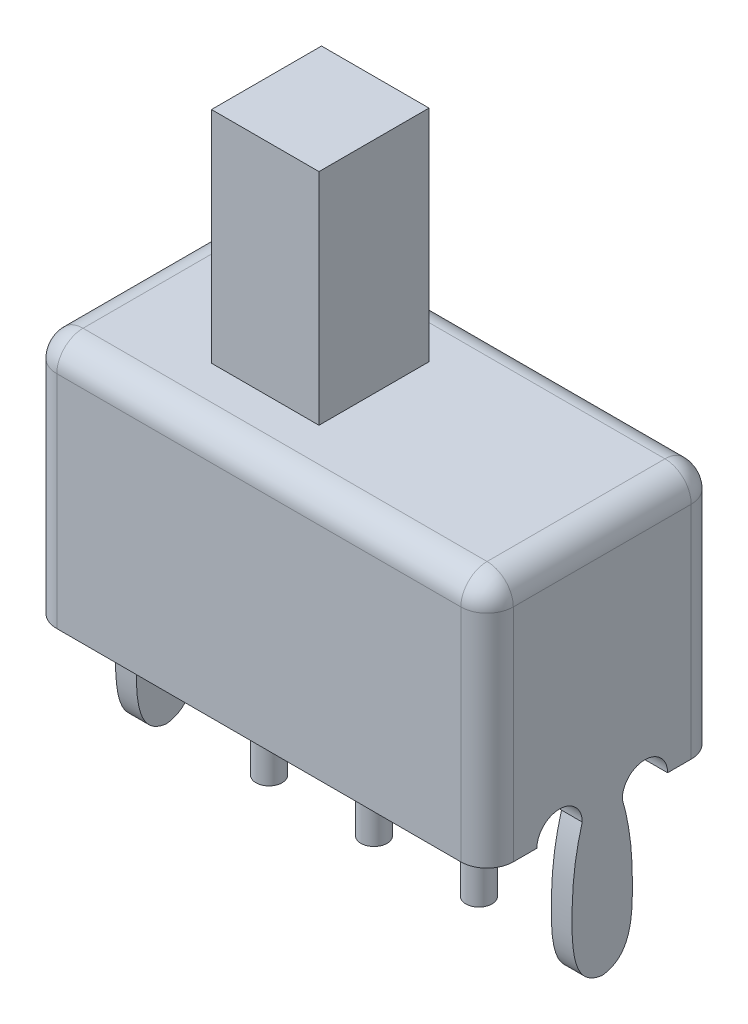
SolidWorks part; units mm, degrees
ref_plane "Front" through (0, 0, 0) normal (0, 0, 1) x (1, 0, 0)
ref_plane "Top" through (0, 0, 0) normal (0, 1, 0) x (1, 0, 0)
ref_plane "Right" through (0, 0, 0) normal (1, 0, 0) x (0, 0, -1)
sketch "Эскиз1" plane through (0, 0, 0) normal (1, 0, 0) x (0, 0, -1)
  line L0 (-1.0075, 7.598) -> (0.9925, 7.598) construction
  line L1 (-2.1951, 0) -> (-2.1951, 4.2075)
  line L2 (-1.6951, 4.7075) -> (-1.0484, 4.7075)
  line L3 (-1.0484, 4.7075) -> (-1.0484, 8.8947)
  line L4 (-1.0484, 8.8947) -> (1.0484, 8.8947)
  line L5 (-2.1951, 0) -> (-1.2455, 0)
  line L6 (0, 8.2215) -> (0, -3.9354) construction
  line L7 (2.1951, 0) -> (1.2455, 0)
  line L8 (2.1951, 0) -> (2.1951, 4.2075)
  line L9 (1.6951, 4.7075) -> (1.0484, 4.7075)
  line L10 (1.0484, 4.7075) -> (1.0484, 8.8947)
  arc A0 (-2.1951, 4.2075) -> (-1.6951, 4.7075) centre (-1.6951, 4.2075) cw
  arc A1 (-1.2455, 0) -> (-0.3816, 0) centre (-0.8135, 0) cw
  arc A2 (1.2455, 0) -> (0.3816, 0) centre (0.8135, 0) ccw
  arc A3 (2.1951, 4.2075) -> (1.6951, 4.7075) centre (1.6951, 4.2075) ccw
  spline S0 degree 3 poles (-0.3816, 0) (-0.5333, -0.5336) (-0.619, -1.409) (-0.5328, -2.6605) (0, -2.7211) knots 0 0 0 0 0.53717 1 1 1 1
  spline S1 degree 3 poles (0.3816, 0) (0.5333, -0.5336) (0.619, -1.409) (0.5328, -2.6605) (0, -2.7211) knots 0 0 0 0 0.53717 1 1 1 1
  point P17 (0, 0)
  point P19 (0, 0)
  point P32 (0, 8.8947)
  dimension "D2" = 0.5
  dimension "D1" = 2
extrude "Бобышка-Вытянуть1" add sketch "Эскиз1" along normal mid plane 8.7
sketch "Эскиз2" plane through (0, 0, 0) normal (0, 0, 1) x (1, 0, 0)
  line L0 (-2.0051, 7.4369) -> (-0.0051, 7.4369) construction
  line L1 (-3.9549, 0) -> (-3.9549, -2.7211)
  line L2 (-3.9549, -2.7211) -> (3.9549, -2.7211)
  line L4 (3.9549, 0) -> (-3.9549, 0)
  line L5 (-2.0487, 4.7075) -> (-2.0487, 8.8947)
  line L6 (-2.0487, 8.8947) -> (-4.35, 8.8947)
  line L7 (-4.35, 8.8947) -> (-4.35, 4.7075)
  line L8 (-4.35, 4.7075) -> (-2.0487, 4.7075)
  line L9 (4.35, 8.8947) -> (-4.35, 8.8947) construction
  line L10 (0, 8.8947) -> (0, 4.7075)
  line L11 (0, 4.7075) -> (4.35, 4.7075)
  line L12 (4.35, 4.7075) -> (4.35, 8.8947)
  line L13 (4.35, 8.8947) -> (0, 8.8947)
  line L14 (0, 2.7711) -> (0, -4.7444) construction
  line L15 (3.9549, 0) -> (3.9549, -2.7211)
  line L16 (4.35, 4.7075) -> (-4.35, 4.7075) construction
  point P6 (0, -2.7211)
  point P20 (0, 0)
  dimension "D1" = 2
extrude "Вырез-Вытянуть1" cut sketch "Эскиз2" along normal through all from surface at -2.1951 starting at face at (0, 2.1038, -2.1951)
fillet "Скругление1" radius 0.5 10 edges at (-4.35, 4.7075, 0) (4.35, 4.7075, 0) (-4.35, 2.1038, -2.1951) (-4.35, 4.5611, -2.0486) (-4.35, 2.1038, 2.1951) (-4.35, 4.5611, 2.0486) (4.35, 2.1038, -2.1951) (4.35, 4.5611, -2.0486) (4.35, 2.1038, 2.1951) (4.35, 4.5611, 2.0486)
sketch "Эскиз3" plane through (0, 0, 0) normal (0, 1, 0) x (1, 0, 0)
  circle A0 centre (0, 0) radius 0.25
  circle A1 centre (-2, 0) radius 0.25
  circle A2 centre (2, 0) radius 0.25
  point P7 (0, 0)
  point P8 (0, 0)
  dimension "D1" = 0.5
  dimension "D2" = 2
  dimension "D3" = 2
extrude "Бобышка-Вытянуть2" add sketch "Эскиз3" against normal blind 7.3 from surface at 4.7075 starting at face at (0, 4.7075, 0)
